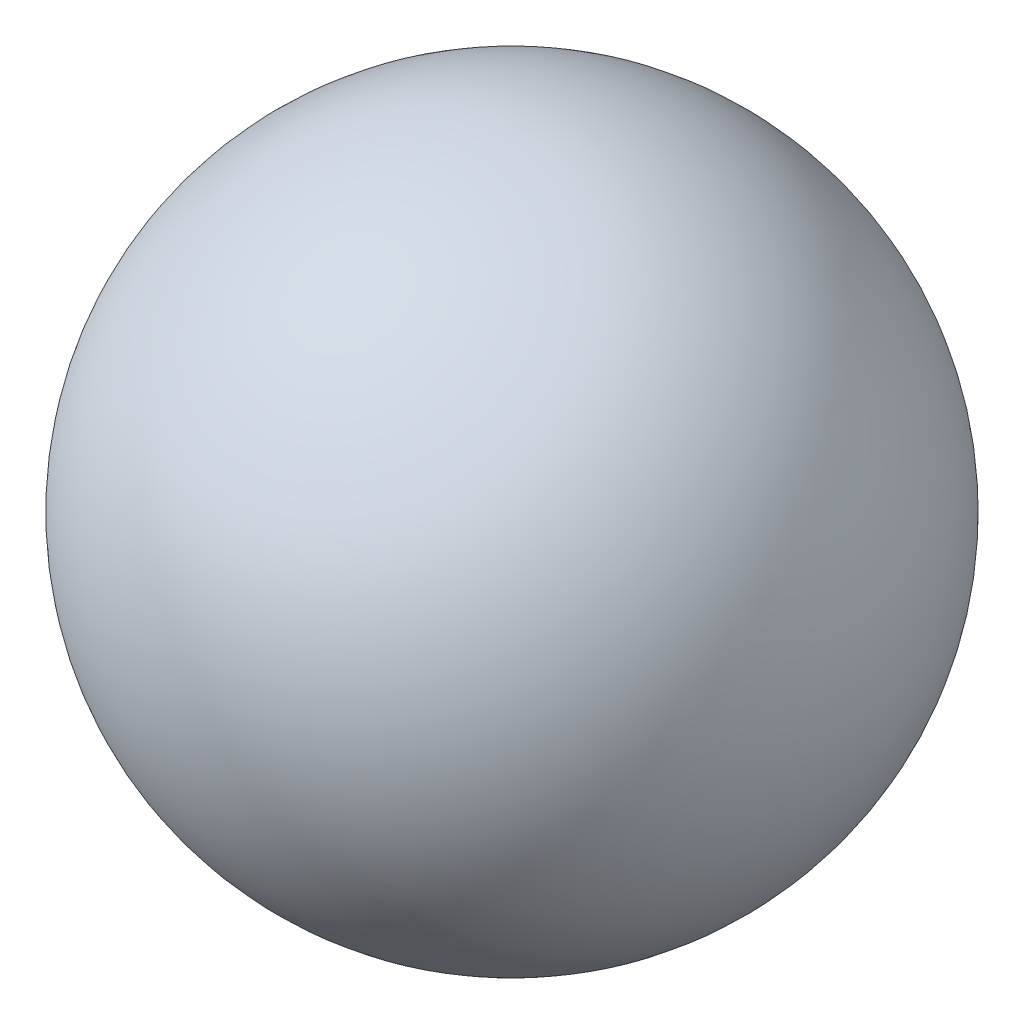
SolidWorks part; units mm, degrees
ref_plane "Alzado" through (0, 0, 0) normal (0, 0, 1) x (1, 0, 0)
ref_plane "Planta" through (0, 0, 0) normal (0, 1, 0) x (1, 0, 0)
ref_plane "Vista lateral" through (0, 0, 0) normal (1, 0, 0) x (0, 0, -1)
sketch "Croquis1" plane through (0, 0, 0) normal (0, 0, 1) x (1, 0, 0)
  line L0 (0, 0) -> (0, 25.4) construction
  line L1 (0, 25.4) -> (0, 22.0097)
  line L2 (0, 3.3903) -> (0, 0)
  arc A0 (0, 25.4) -> (0, 0) centre (0, 12.7) cw
  arc A2 (0, 22.0097) -> (0, 3.3903) centre (0, 12.7) cw
  dimension "D1" = 25.4
revolve "Revolución1" add sketch "Croquis1" angle 360 about L0
